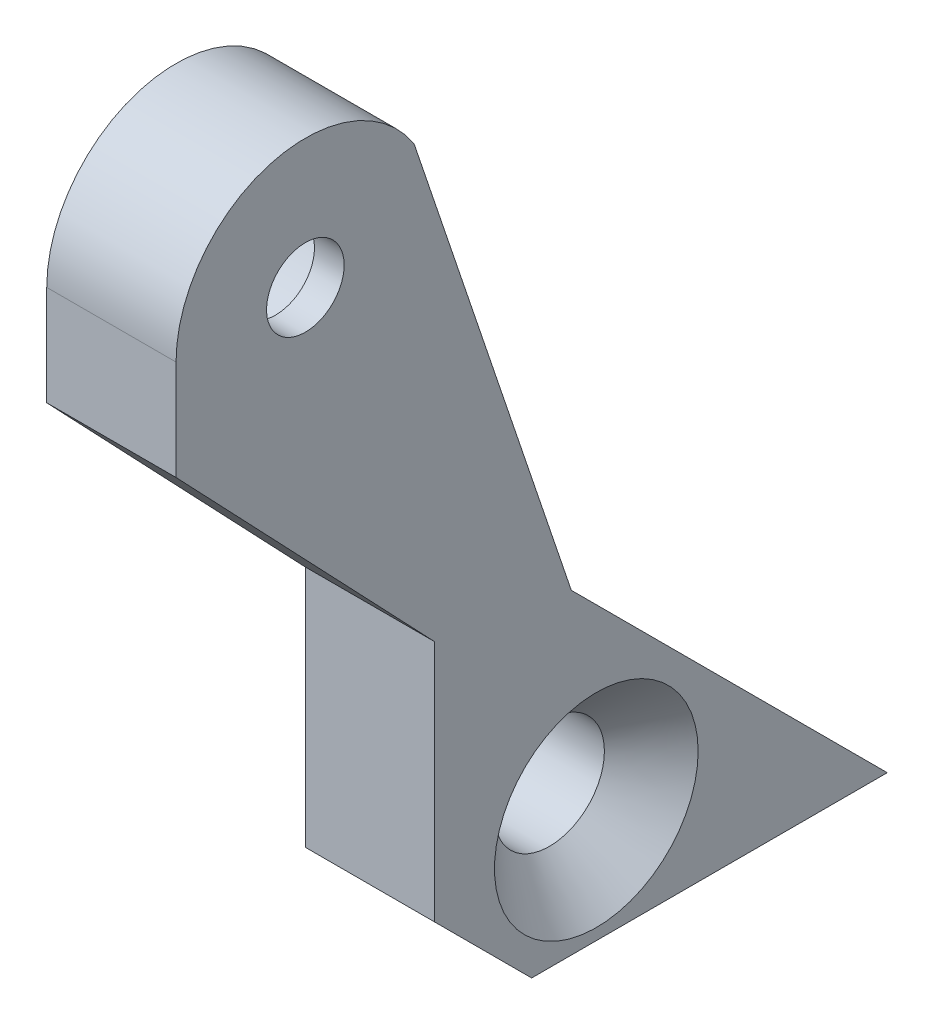
SolidWorks part; units mm, degrees
ref_plane "Plano frontal" through (0, 0, 0) normal (0, 0, 1) x (1, 0, 0)
ref_plane "Plano superior" through (0, 0, 0) normal (0, 1, 0) x (1, 0, 0)
ref_plane "Plano direito" through (0, 0, 0) normal (1, 0, 0) x (0, 0, -1)
sketch "Esboço1" plane through (0, 0, 0) normal (1, 0, 0) x (0, 0, -1)
  line L0 (0, 0) -> (0, 3.0918)
  line L1 (7.362, 5.2591) -> (12.226, -9.1341)
  line L10 (0, 0) -> (8, -8.3993)
  line L11 (8, -8.3993) -> (8, -15.9082)
  line L12 (11, -18.9082) -> (22, -18.9082)
  line L13 (22, -18.9082) -> (12.226, -9.1341)
  line L14 (8, -15.9082) -> (11, -18.9082)
  arc A0 (0, 3.0918) -> (7.362, 5.2591) centre (4, 3.0918) cw
  point P8 (0, 0)
  point P11 (0, 0)
  point P12 (8, -3)
  point P13 (8, -3)
  point P14 (12.8339, -8.466)
  point P15 (12.8612, -8.2535)
  point P16 (14.5622, -10.9808)
  point P17 (15.3892, -11.8453)
  point P18 (13.6182, -10.6828)
  point P19 (13.4062, -9.3015)
  point P20 (0, 0)
  point P21 (0, 0)
  point P22 (12.226, -9.1341)
  point P23 (0, 0)
  dimension "D1" = 4
  dimension "D3" = 45
  dimension "D2" = 8
  dimension "D6" = 22
  dimension "D7" = 18
  dimension "D8" = 3
  dimension "D9" = 3
extrude "Ressalto-extrusão1" add sketch "Esboço1" along normal blind 4
hole_wizard "Furo de diâmetro Ø6.0 (6)1" positions "Esboço2" profile "Esboço3" hole size "Ø6.0" standard "ISO"
sketch "Esboço2" plane through (0, 0, 0) normal (-1, 0, 0) x (0, 0, 1)
  arc A0 (0, 3.0918) -> (-7.362, 5.2591) centre (-4, 3.0918) ccw construction
  point P0 (-4, 3.0918)
sketch "Esboço3" plane through (0, 3.0918, -4) normal (0, 1, 0) x (0, 0, 1)
  line L0 (0, 0) -> (0, 3.8026)
  line L1 (0, 3.8026) -> (3, 2)
  line L2 (3, 2) -> (3, 0)
  line L5 (3, 0) -> (0, 0)
  line L10 (0, 3.8026) -> (-3, 2) construction
  line L11 (0, -6.35) -> (0, 107.95) construction
  dimension "Hole Dia." = 6
  dimension "Hole Depth" = 2
  dimension "Drill Angle" = 118
sketch "Esboço4" plane through (4, 0, 0) normal (1, 0, 0) x (0, 0, -1)
  circle A0 centre (4, 3.0918) radius 1.2
  arc A2 (7.362, 5.2591) -> (0, 3.0918) centre (4, 3.0918) ccw construction
  dimension "D1" = 2.4
extrude "Corte-extrusão1" cut sketch "Esboço4" against normal through all
hole_wizard "Escareado para parafuso com cabeça escareada chata de M31" positions "Esboço5" profile "Esboço6" countersink size "M3" standard "ISO" end condition through all
sketch "Esboço5" plane through (4, 0, 0) normal (1, 0, 0) x (0, 0, -1)
  line L0 (11, -18.9082) -> (22, -18.9082) construction
  line L1 (8, -8.3993) -> (8, -15.9082) construction
  point P0 (13, -15.4082)
  dimension "D1" = 3.5
  dimension "D2" = 5
sketch "Esboço6" plane through (4, -15.4082, -13) normal (0, 1, 0) x (0, 0, -1)
  line L0 (0, 0) -> (0, 4)
  line L1 (0, 4) -> (1.7, 4)
  line L2 (1.7, 4) -> (1.7, 1.45)
  line L3 (1.7, 1.45) -> (3.15, 0)
  line L5 (3.15, 0) -> (0, 0)
  line L6 (-1.7, 1.45) -> (-3.15, 0) construction
  line L11 (0, -6.35) -> (0, 107.95) construction
  dimension "Thru Hole Dia." = 3.4
  dimension "Thru Hole Depth" = 4
  dimension "Near C'Sink Dia." = 6.3
  dimension "Near C'Sink Angle" = 90
